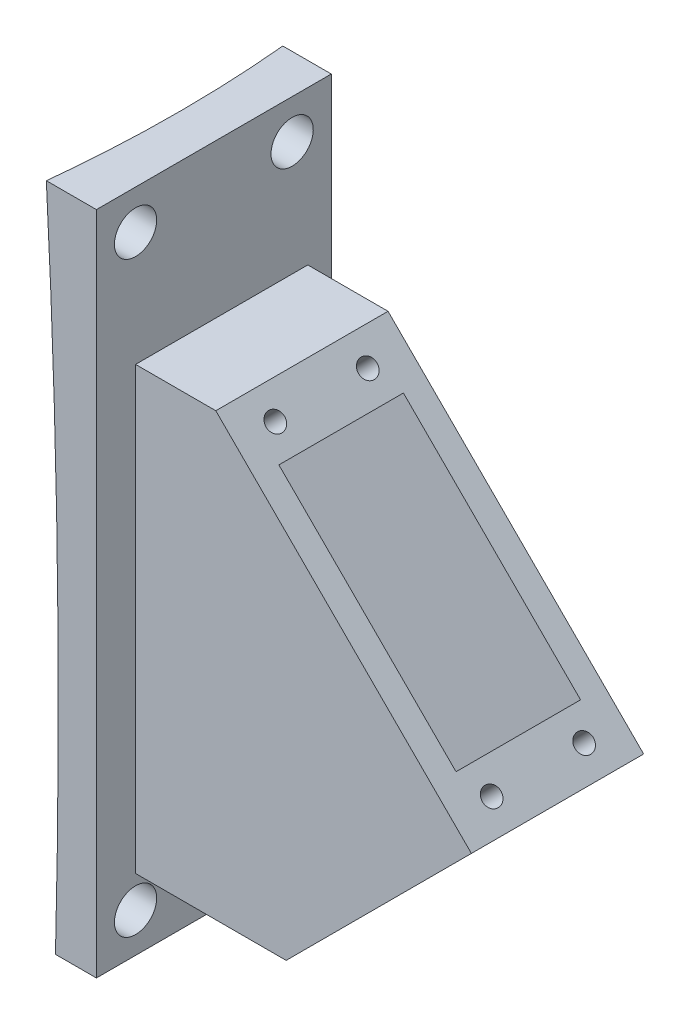
SolidWorks part; units mm, degrees
material "Nylon 101"
ref_plane "Front Plane" through (0, 0, 0) normal (0, 0, 1) x (1, 0, 0)
ref_plane "Top Plane" through (0, 0, 0) normal (0, 1, 0) x (1, 0, 0)
ref_plane "Right Plane" through (0, 0, 0) normal (1, 0, 0) x (0, 0, -1)
sketch "Sketch1" plane through (0, 0, 0) normal (1, 0, 0) x (0, 0, -1)
  line L1 (-7.62, -23.625) -> (7.62, -23.625)
  line L2 (-7.62, -23.625) -> (-7.62, 23.625)
  line L3 (-7.62, 23.625) -> (7.62, 23.625)
  line L4 (7.62, -23.625) -> (7.62, 23.625)
  line L5 (-7.62, -23.625) -> (7.62, 23.625) construction
  line L6 (-7.62, 23.625) -> (7.62, -23.625) construction
  point P0 (0, 0)
  dimension "D1" = 15.24
  dimension "D2" = 47.25
extrude "Boss-Extrude1" add sketch "Sketch1" along normal blind 29
sketch "Sketch8" plane through (0, 0, 0) normal (0, 1, 0) x (1, 0, 0)
  line L0 (8.89, -7.62) -> (8.89, 7.62) construction
  line L1 (29, -7.62) -> (0, -7.62) construction
  line L2 (29, 7.62) -> (0, 7.62) construction
  line L4 (0, -7.62) -> (0, 7.62) construction
  line L5 (8.89, 0) -> (-1363.98, 0) construction
  line L6 (-1363.98, 509.27) -> (-1363.98, -509.27)
  ellipse E0 centre (-1363.98, 0) end of major axis (8.89, 0) minor radius 509.27 (-1363.98, -509.27) -> (-1363.98, 509.27) ccw
  point P14 (-1363.98, 0)
  dimension "D1" = 8.89
  dimension "D2" = 1372.87
  dimension "D3" = 1018.54
revolve "Cut-Revolve1" cut sketch "Sketch8" angle 360 about L6
sketch "Sketch9" plane through (0, 0, 7.62) normal (0, 0, 1) x (1, 0, 0)
  line L0 (29, -23.625) -> (57.2937, -23.625)
  line L1 (57.2937, -23.625) -> (29, 23.625)
  line L2 (29, 23.625) -> (29, -23.625)
extrude "Boss-Extrude2" add sketch "Sketch9" against normal blind 15.24
ref_point "Point1"
sketch "Sketch11" plane through (0, 0, -7.62) normal (0, 0, -1) x (-1, 0, 0)
  line L0 (-8.533, 23.625) -> (-35.4738, 50.5658)
  line L1 (1364.0974, -1372.87) -> (-8.7726, 0) construction
  line L2 (-35.4738, 50.5658) -> (-71.0711, 14.9685)
  line L3 (-71.0711, 14.9685) -> (-48.5444, -9.0138)
  line L4 (-8.533, 23.625) -> (-28.8894, 23.625)
  line L5 (-28.8894, 23.625) -> (-48.5444, -9.0138)
  line L6 (-57.2937, -23.625) -> (-29, 23.625) construction
  dimension "D1" = 38.1
  dimension "D2" = 38.1
extrude "Boss-Extrude3" add sketch "Sketch11" against normal blind 27.94 from offset 6.35
sketch "Sketch12" plane through (43.0198, 43.0198, 0) normal (0.7071, 0.7071, 0) x (0, 0, -1)
  line L0 (13.97, 10.6717) -> (13.97, -39.6705) construction
  line L1 (-10.1003, 5.8206) -> (10.1003, 5.8206)
  line L2 (-10.1003, 5.8206) -> (-10.1003, -34.8194)
  line L3 (-10.1003, -34.8194) -> (10.1003, -34.8194)
  line L4 (10.1003, 5.8206) -> (10.1003, -34.8194)
  line L5 (-10.1003, 5.8206) -> (10.1003, -34.8194) construction
  line L6 (-10.1003, -34.8194) -> (10.1003, 5.8206) construction
  line L7 (-13.97, 10.6717) -> (13.97, 10.6717) construction
  point P0 (0, -14.4994)
  point P6 (10.1003, -14.4994)
  point P9 (13.97, -14.4994)
  point P10 (0, 5.8206)
  point P13 (0, 10.6717)
  dimension "D1" = 40.64
  dimension "D2" = 20.2006
sketch "Sketch13" plane through (0, 0, -7.62) normal (0, 0, -1) x (-1, 0, 0)
  line L0 (-61.6723, 5.5697) -> (-8.533, -23.625)
  line L1 (-8.533, -23.625) -> (-25.0252, -53.6437)
  line L2 (-25.0252, -53.6437) -> (-79.4171, -23.7609)
  line L3 (-79.4171, -23.7609) -> (-61.6723, 5.5697)
extrude "Cut-Extrude4" cut sketch "Sketch13" against normal through all both and the other way through all
sketch "Sketch15" plane through (0, 0, 7.62) normal (0, 0, 1) x (1, 0, 0)
  line L0 (8.533, -23.625) -> (45.2091, -3.4752) construction
  line L1 (13.867, 72.765) -> (1.133, 72.765)
  line L2 (13.867, 72.765) -> (13.867, -35.185)
  line L3 (13.867, -35.185) -> (1.133, -35.185)
  line L4 (1.133, 72.765) -> (1.133, -35.185)
  dimension "D1" = 12.7
  dimension "D2" = 107.95
  dimension "D3" = 5.334
extrude "Boss-Extrude4" add sketch "Sketch15" against normal blind 38.1 from offset 12.7
sketch "Sketch16" plane through (0, 0, 0) normal (0, 1, 0) x (1, 0, 0)
  line L0 (8.771, -44.3468) -> (8.771, 44.3468) construction
  line L1 (8.771, 0) -> (-1364.099, 0) construction
  line L2 (-1364.099, 509.27) -> (-1364.099, -509.27)
  ellipse E0 centre (-1364.099, 0) end of major axis (8.771, 0) minor radius 509.27 (-1364.099, -509.27) -> (-1364.099, 509.27) ccw
  point P6 (-1364.099, 0)
  dimension "D1" = 1372.87
  dimension "D2" = 1018.54
  dimension "D3" = 88.6936
revolve "Cut-Revolve2" cut sketch "Sketch16" angle 360 about L2
sketch "Sketch17" plane through (13.867, 0, 0) normal (1, 0, 0) x (0, 0, -1)
  line L0 (-20.32, -35.185) -> (-20.32, 72.765) construction
  line L1 (17.78, -35.185) -> (-20.32, -35.185) construction
  line L2 (17.78, -35.185) -> (17.78, 72.765) construction
  line L3 (17.78, 72.765) -> (-20.32, 72.765) construction
  circle A0 centre (-13.97, -28.835) radius 3.429
  circle A1 centre (-13.97, 66.415) radius 3.429
  circle A2 centre (11.43, 66.415) radius 3.429
  circle A3 centre (11.43, -28.835) radius 3.429
  dimension "D1" = 6.858
  dimension "D3" = 6.35
  dimension "D6" = 6.35
  dimension "D7" = 6.35
  dimension "D2" = 6.35
  dimension "D4" = 2
  dimension "D5" = 2
extrude "Cut-Extrude6" cut sketch "Sketch17" against normal through all
sketch "Sketch19" plane through (0, 0, 7.62) normal (0, 0, 1) x (1, 0, 0)
  line L4 (28.8894, 23.625) -> (13.867, 23.625)
  line L5 (13.867, 23.625) -> (13.867, -20.6945)
  line L6 (13.867, -20.6945) -> (45.2091, -3.4752)
  line L9 (13.867, 23.625) -> (13.867, -20.6945)
  line L10 (13.867, -20.6945) -> (45.2091, -3.4752)
  line L12 (28.8894, 23.625) -> (13.867, 23.625)
  line L14 (45.2091, -3.4752) -> (28.8894, 23.625)
  line L15 (45.2091, -3.4752) -> (28.8894, 23.625)
  dimension "D1" = 0
extrude "Boss-Extrude9" add sketch "Sketch19" along normal up to surface (6.35 mm away) up to face at (41.4932, 18.6297, 13.97)
sketch "Sketch20" plane through (0, 0, -7.62) normal (0, 0, -1) x (-1, 0, 0)
  line L4 (-45.2091, -3.4752) -> (-13.867, -20.6945)
  line L5 (-13.867, -20.6945) -> (-13.867, 23.625)
  line L6 (-13.867, 23.625) -> (-28.8894, 23.625)
  line L8 (-45.2091, -3.4752) -> (-13.867, -20.6945)
  line L9 (-13.867, -20.6945) -> (-13.867, 23.625)
  line L12 (-13.867, 23.625) -> (-28.8894, 23.625)
  line L14 (-28.8894, 23.625) -> (-45.2091, -3.4752)
  line L15 (-28.8894, 23.625) -> (-45.2091, -3.4752)
  dimension "D1" = 0
extrude "Boss-Extrude10" add sketch "Sketch20" along normal up to surface (6.35 mm away) up to face at (41.4932, 18.6297, -13.97)
extrude "Cut-Extrude8" cut sketch "Sketch12" against normal blind 38.1
sketch "Sketch21" plane through (43.0198, 43.0198, 0) normal (0.7071, 0.7071, 0) x (0, 0, -1)
  line L1 (-13.97, -39.6705) -> (13.97, -39.6705)
  line L2 (-13.97, -39.6705) -> (-13.97, 10.6717)
  line L3 (-13.97, 10.6717) -> (13.97, 10.6717)
  line L4 (13.97, -39.6705) -> (13.97, 10.6717)
extrude "Cut-Extrude9" cut sketch "Sketch21" against normal blind 8 contours L1 L4 L3 L2
sketch "Sketch22" plane through (28.0513, -28.0513, 0) normal (-0.7071, 0.7071, 0) x (0, 0, 1)
  line L1 (13.97, 60.8391) -> (-13.97, 60.8391)
  line L2 (13.97, 60.8391) -> (13.97, 52.8391)
  line L3 (13.97, 52.8391) -> (-13.97, 52.8391)
  line L4 (-13.97, 60.8391) -> (-13.97, 52.8391)
extrude "Cut-Extrude10" cut sketch "Sketch22" against normal blind 2.54
sketch "Sketch23" plane through (0, 0, 0) normal (0, 0, 1) x (1, 0, 0)
  line L0 (29.8169, 44.9089) -> (26.8832, 47.8426)
  line L1 (26.8832, 47.8426) -> (13.867, 47.8426)
  line L2 (13.867, -35.185) -> (13.867, 72.765) construction
  line L3 (13.867, 47.8426) -> (13.867, 28.959)
  line L4 (13.867, 28.959) -> (29.8169, 44.9089)
  line L5 (65.5913, 9.1346) -> (13.867, -20.6945)
  line L6 (13.867, -20.6945) -> (13.867, -23.6743)
  line L8 (68.3479, 6.3779) -> (65.5913, 9.1346)
  line L9 (68.3479, 6.3779) -> (61.984, 12.7419) construction
  line L10 (26.8832, 47.8426) -> (33.2472, 41.4787) construction
  line L12 (68.3479, 6.3779) -> (38.2958, -23.6743)
  line L13 (38.2958, -23.6743) -> (13.867, -23.6743)
  point P16 (38.2858, -23.9444)
  point P18 (13.867, -24.3815)
  dimension "D1" = 9
  dimension "D2" = 9
extrude "Boss-Extrude11" add sketch "Sketch23" along normal mid plane 27.94
sketch "Sketch24" plane through (12.4167, -21.5309, 0) normal (-0.4996, 0.8663, 0) x (0.8663, 0.4996, 0)
  line L4 (41.7088, -10.1003) -> (41.7088, 10.1003)
  line L5 (41.7088, 10.1003) -> (30.2173, 10.1003)
  line L6 (30.2173, 10.1003) -> (30.2173, -10.1003)
  line L7 (30.2173, -10.1003) -> (41.7088, -10.1003)
  line L8 (41.7088, -10.1003) -> (41.7088, 10.1003)
  line L9 (41.7088, 10.1003) -> (30.2173, 10.1003)
  line L10 (30.2173, 10.1003) -> (30.2173, -10.1003)
  line L11 (30.2173, -10.1003) -> (41.7088, -10.1003)
  dimension "D1" = 0
extrude "Cut-Extrude11" cut sketch "Sketch24" against normal through all
sketch "Sketch25" plane through (37.3629, 37.3629, 0) normal (0.7071, 0.7071, 0) x (0, 0, -1)
  line L0 (-7.5, 10.3206) -> (7.5, 10.3206) construction
  line L1 (0, 14.8206) -> (0, 5.8206) construction
  line L2 (-13.97, 14.8206) -> (13.97, 14.8206) construction
  line L3 (10.1003, 5.8206) -> (-10.1003, 5.8206) construction
  line L4 (-7.5, -39.3194) -> (7.5, -39.3194) construction
  line L5 (0, -34.8194) -> (0, -43.8194) construction
  line L6 (-10.1003, -34.8194) -> (10.1003, -34.8194) construction
  line L9 (-13.97, -43.8194) -> (13.97, -43.8194) construction
  circle A0 centre (-7.5, 10.3206) radius 1.5
  circle A1 centre (7.5, 10.3206) radius 1.5
  circle A2 centre (-7.5, -39.3194) radius 1.5
  circle A3 centre (7.5, -39.3194) radius 1.5
  point P4 (0, 10.3206)
  point P12 (0, 10.3206)
  point P17 (0, -39.3194)
  point P20 (0, -39.3194)
  point P21 (0, -34.8194)
  point P24 (0, -43.8194)
  point P25 (0, 0)
  point P27 (0, 0)
  point P28 (7.5, -39.3194)
  point P29 (-7.5, -36.9501)
  point P31 (0, -43.8194)
  dimension "D1" = 3
  dimension "D2" = 15
extrude "Cut-Extrude12" cut sketch "Sketch25" against normal blind 18
